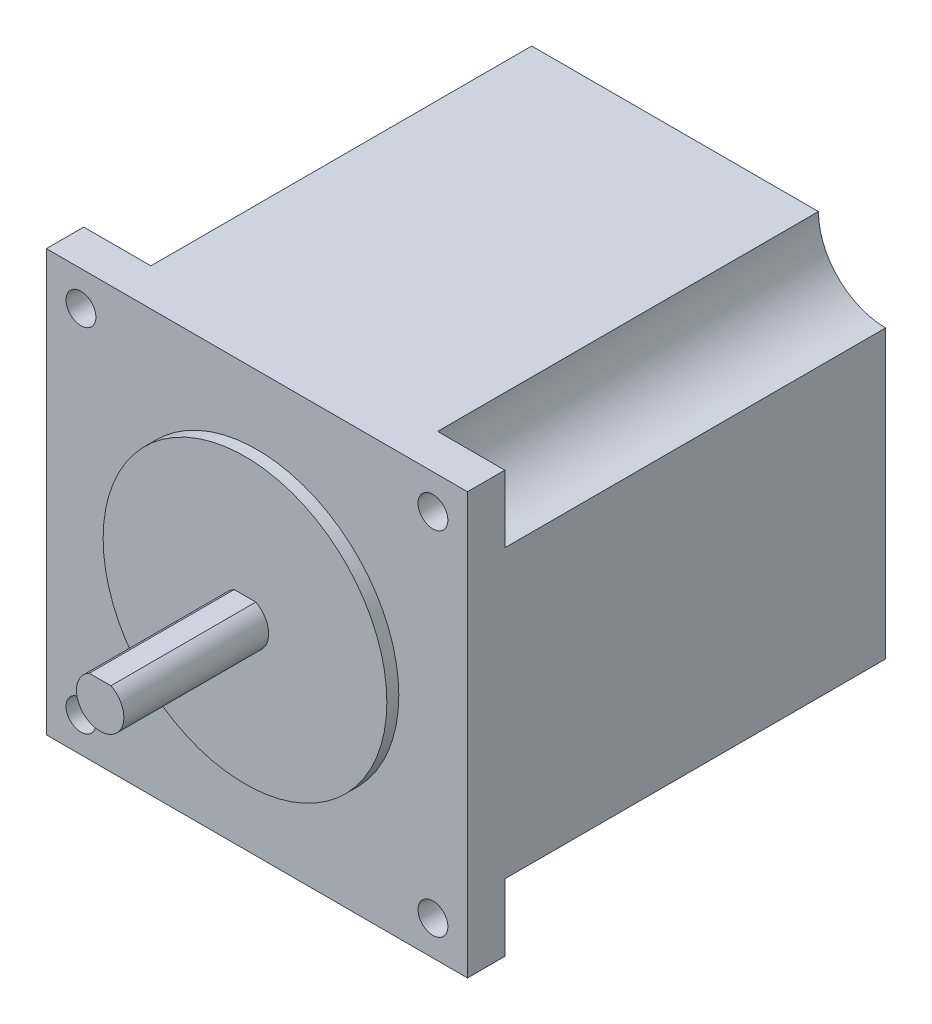
SolidWorks part; units mm, degrees
ref_plane "Front Plane" through (0, 0, 0) normal (0, 0, 1) x (1, 0, 0)
ref_plane "Top Plane" through (0, 0, 0) normal (0, 1, 0) x (1, 0, 0)
ref_plane "Right Plane" through (0, 0, 0) normal (1, 0, 0) x (0, 0, -1)
sketch "Sketch1" plane through (0, 0, 0) normal (0, 0, 1) x (1, 0, 0)
  line L1 (-28.2, -28.2) -> (28.2, -28.2)
  line L2 (-28.2, -28.2) -> (-28.2, 28.2)
  line L3 (-28.2, 28.2) -> (28.2, 28.2)
  line L4 (28.2, -28.2) -> (28.2, 28.2)
  line L5 (-28.2, -28.2) -> (28.2, 28.2) construction
  line L6 (-28.2, 28.2) -> (28.2, -28.2) construction
  point P0 (0, 0)
  dimension "D1" = 56.4
extrude "Boss-Extrude1" add sketch "Sketch1" along normal blind 56
sketch "Sketch2" plane through (0, 0, 56) normal (0, 0, 1) x (1, 0, 0)
  circle A0 centre (0, 0) radius 19
  dimension "D1" = 38
extrude "Boss-Extrude2" add sketch "Sketch2" along normal blind 1.6
sketch "Sketch3" plane through (0, 0, 57.6) normal (0, 0, 1) x (1, 0, 0)
  circle A0 centre (0, 0) radius 3.175
  dimension "D1" = 6.35
extrude "Boss-Extrude3" add sketch "Sketch3" along normal blind 19.4
sketch "Sketch4" plane through (0, 0, 77) normal (0, 0, 1) x (1, 0, 0)
  line L0 (-1.4491, 2.825) -> (1.4491, 2.825)
  line L1 (0, -3.175) -> (0, 2.825) construction
  circle A1 centre (0, 0) radius 3.175
  circle A2 centre (0, 0) radius 3.175
  circle M3 centre (0, 0) radius 3.175
  dimension "D2" = 6
extrude "Cut-Extrude1" cut sketch "Sketch4" against normal blind 19.4 contours L0 M3
sketch "Sketch5" plane through (0, 0, 56) normal (0, 0, 1) x (1, 0, 0)
  line L0 (0, 0) -> (-50000, 0) construction
  line L1 (-23.57, 23.57) -> (23.57, 23.57) construction
  line L2 (-23.57, 23.57) -> (-23.57, -23.57) construction
  line L3 (-23.57, -23.57) -> (23.57, -23.57) construction
  line L4 (23.57, 23.57) -> (23.57, -23.57) construction
  line L5 (-23.57, 23.57) -> (23.57, -23.57) construction
  line L6 (-23.57, -23.57) -> (23.57, 23.57) construction
  line L7 (0, 0) -> (0, 50000) construction
  circle A0 centre (23.57, 23.57) radius 2
  circle A1 centre (-23.57, 23.57) radius 2
  circle A2 centre (23.57, -23.57) radius 2
  circle A3 centre (-23.57, -23.57) radius 2
  point P0 (0, 0)
  dimension "D2" = 4
  dimension "D1" = 47.14
extrude "Cut-Extrude2" cut sketch "Sketch5" against normal through all
sketch "Sketch6" plane through (0, 0, 0) normal (0, 0, -1) x (-1, 0, 0)
  line L0 (0, 0) -> (0, -50000) construction
  line L1 (0, 0) -> (-50000, 0) construction
  circle A0 centre (-28.2, 28.2) radius 9
  circle A1 centre (-28.2, -28.2) radius 9
  circle A2 centre (28.2, -28.2) radius 9
  circle A3 centre (28.2, 28.2) radius 9
  dimension "D1" = 18
extrude "Cut-Extrude3" cut sketch "Sketch6" against normal blind 51
equation "\"External Length\" = 56.4mm"
equation "\"Length Between Fastener Holes\" = 47.14mm"
equation "\"Width\" = 56mm"
equation "\"Pinion Length\" = 19.4mm"
equation "\"Platform Extrusion\" = 1.6mm"
equation "\"Cut out\" = 6mm"
equation "\"Pinion Diameter\" = 6.35mm"
equation "\"Platfomr Diatmeter\" = 38mm"
equation "\"D1@Sketch1\"=\"External Length\""
equation "\"D1@Boss-Extrude1\"=\"Width\""
equation "\"D1@Sketch2\"=\"Platfomr Diatmeter\""
equation "\"D1@Boss-Extrude2\"=\"Platform Extrusion\""
equation "\"Cut out length\" = \"Pinion Length\""
equation "\"D1@Sketch3\"=\"Pinion Diameter\""
equation "\"D1@Boss-Extrude3\"=\"Pinion Length\""
equation "\"D2@Sketch4\"=\"Cut out\""
equation "\"D1@Cut-Extrude1\"=\"Cut out length\""
equation "\"D1@Sketch5\"=\"Length Between Fastener Holes\""
equation "\"Fastener hole\"= 4mm"
equation "\"fastener hole depth\"= 4.5mm"
equation "\"D1@Cut-Extrude2\"=\"fastener hole depth\""
equation "\"D2@Sketch5\"=\"Fastener hole\""
equation "\"D1@Cut-Extrude3\"=\"Width\"-5"
